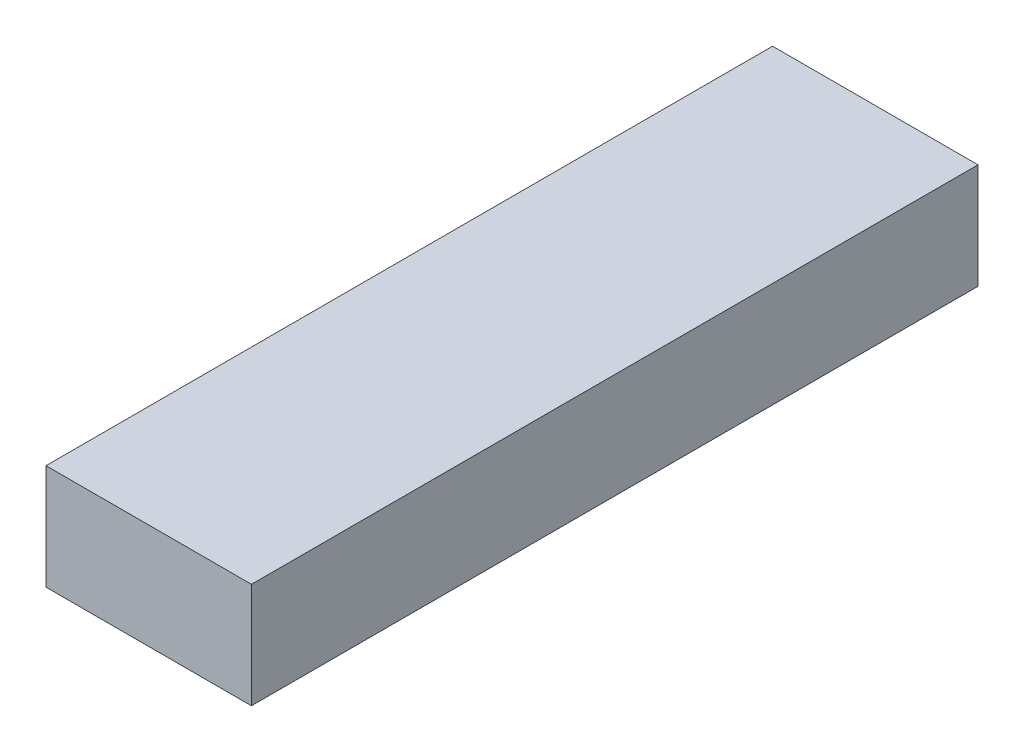
SolidWorks part; units mm, degrees
ref_plane "Front Plane" through (0, 0, 0) normal (0, 0, 1) x (1, 0, 0)
ref_plane "Top Plane" through (0, 0, 0) normal (0, 1, 0) x (1, 0, 0)
ref_plane "Right Plane" through (0, 0, 0) normal (1, 0, 0) x (0, 0, -1)
sketch "Sketch1" plane through (0, 0, 0) normal (0, 0, 1) x (1, 0, 0)
  line L1 (-20.5, 10.5) -> (20.5, 10.5)
  line L2 (-20.5, 10.5) -> (-20.5, -10.5)
  line L3 (-20.5, -10.5) -> (20.5, -10.5)
  line L4 (20.5, 10.5) -> (20.5, -10.5)
  line L5 (-20.5, 10.5) -> (20.5, -10.5) construction
  line L6 (-20.5, -10.5) -> (20.5, 10.5) construction
  point P0 (0, 0)
extrude "Boss-Extrude1" add sketch "Sketch1" along normal blind 145
